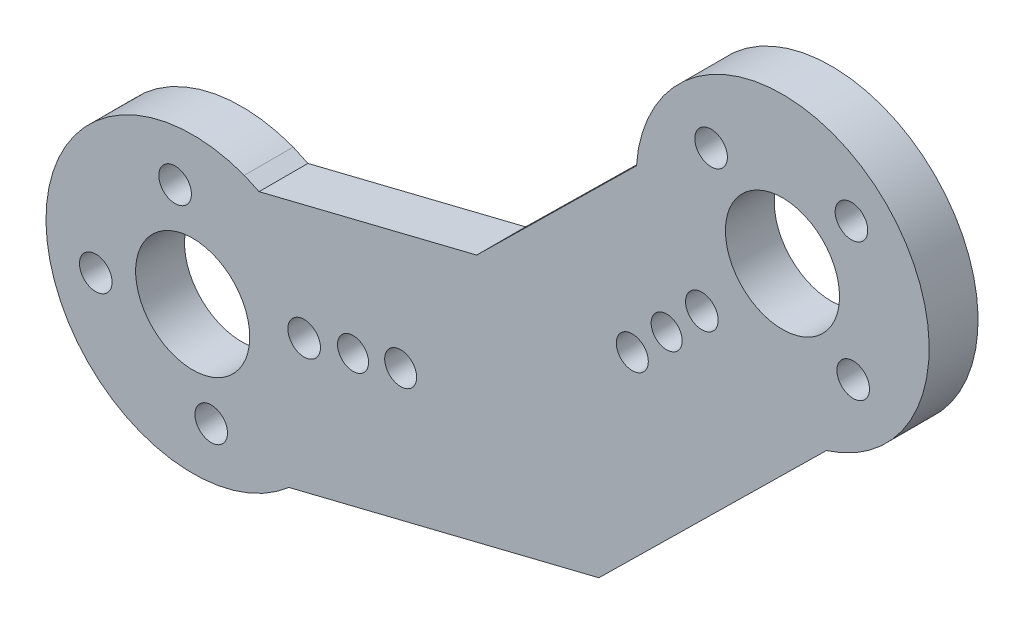
SolidWorks part; units mm, degrees
ref_plane "Front Plane" through (0, 0, 0) normal (0, 0, 1) x (1, 0, 0)
ref_plane "Top Plane" through (0, 0, 0) normal (0, 1, 0) x (1, 0, 0)
ref_plane "Right Plane" through (0, 0, 0) normal (1, 0, 0) x (0, 0, -1)
sketch "Sketch1" plane through (0, 0, 0) normal (0, 0, 1) x (1, 0, 0)
  line L1 (-50.0906, 20.2464) -> (-63.4434, 16.9398)
  line L2 (-63.4434, 16.9398) -> (-64.3482, 17.3556)
  line L3 (-42.5948, 6.848) -> (-28.6337, 20.5872)
  line L4 (-42.5948, 6.848) -> (-61.6083, 2.1396)
  line L5 (-40.2859, 29.8952) -> (-40.1668, 30.8838)
  line L6 (-50.0906, 20.2464) -> (-40.2859, 29.8952)
  circle A0 centre (-27.0988, 33.5529) radius 1
  circle A1 centre (-67.5142, 8.9308) radius 3.5
  arc A2 (-64.3482, 17.3556) -> (-61.6083, 2.1396) centre (-67.5142, 8.9308) ccw
  circle A3 centre (-60.6758, 10.5359) radius 1
  circle A4 centre (-66.3777, 3.1413) radius 1
  circle A5 centre (-68.5926, 14.7314) radius 1
  circle A6 centre (-57.6758, 11.2277) radius 0.9526
  circle A7 centre (-54.7535, 11.9064) radius 0.9803
  circle A8 centre (-40.5435, 19.8562) radius 0.9803
  circle A9 centre (-38.4361, 21.9914) radius 0.9526
  circle A10 centre (-35.7097, 33.1277) radius 1
  circle A11 centre (-26.9918, 25.1757) radius 1
  circle A12 centre (-36.2768, 24.1859) radius 1
  circle A13 centre (-73.4605, 7.6158) radius 1
  arc A14 (-40.1668, 30.8838) -> (-28.6337, 20.5872) centre (-31.3308, 29.1736) cw
  circle A15 centre (-31.3308, 29.1736) radius 3.5
extrude "Бобышка-Вытянуть6" add sketch "Sketch1" along normal blind 3
